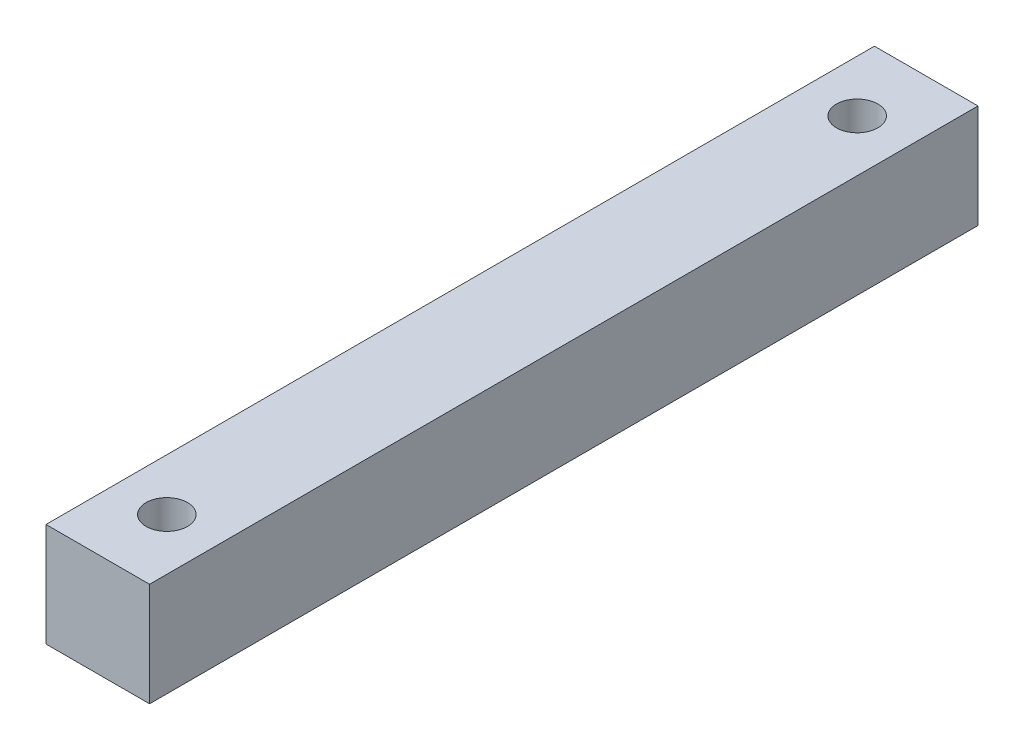
SolidWorks part; units mm, degrees
ref_plane "前视基准面" through (0, 0, 0) normal (0, 0, 1) x (1, 0, 0)
ref_plane "上视基准面" through (0, 0, 0) normal (0, 1, 0) x (1, 0, 0)
ref_plane "右视基准面" through (0, 0, 0) normal (1, 0, 0) x (0, 0, -1)
other "Configuration Table"
sketch "草图1" plane through (0, 0, 0) normal (0, 0, 1) x (1, 0, 0)
  line L1 (0, 0) -> (15, 0)
  line L2 (0, 0) -> (0, -15)
  line L3 (0, -15) -> (15, -15)
  line L4 (15, 0) -> (15, -15)
  dimension "D1" = 15
  dimension "D2" = 15
extrude "凸台-拉伸1" add sketch "草图1" along normal blind 120
sketch "草图2" plane through (0, 0, 0) normal (0, 1, 0) x (1, 0, 0)
  line L0 (7.5, 0) -> (7.5, -120) construction
  line L1 (15, 0) -> (0, 0) construction
  line L2 (15, -120) -> (0, -120) construction
  circle A0 centre (7.5, -10) radius 3
  circle A1 centre (7.5, -110) radius 3
  dimension "D1" = 6
  dimension "D2" = 6
  dimension "D3" = 100
  dimension "D4" = 10
extrude "切除-拉伸1" cut sketch "草图2" against normal through all
